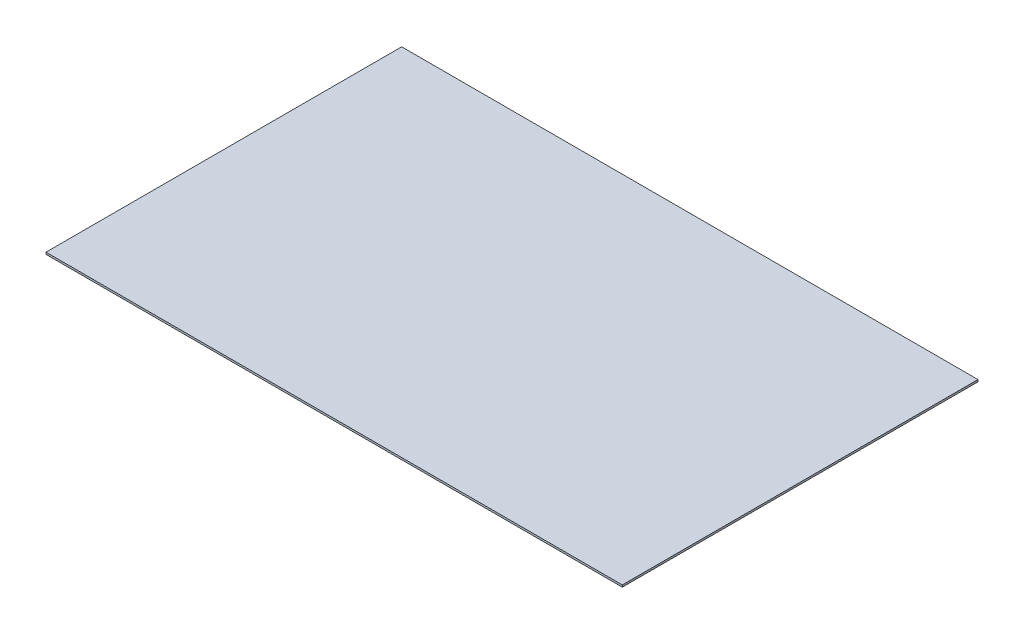
SolidWorks part; units mm, degrees
ref_plane "Front Plane" through (0, 0, 0) normal (0, 0, 1) x (1, 0, 0)
ref_plane "Top Plane" through (0, 0, 0) normal (0, 1, 0) x (1, 0, 0)
ref_plane "Right Plane" through (0, 0, 0) normal (1, 0, 0) x (0, 0, -1)
sketch "Sketch1" plane through (0, 0, 0) normal (0, 1, 0) x (1, 0, 0)
  line L0 (-437.5, 270) -> (437.5, 270)
  line L1 (-437.5, 270) -> (-437.5, -270)
  line L2 (-437.5, -270) -> (437.5, -270)
  line L3 (437.5, 270) -> (437.5, -270)
extrude "Boss-Extrude1" add sketch "Sketch1" along normal blind 3
